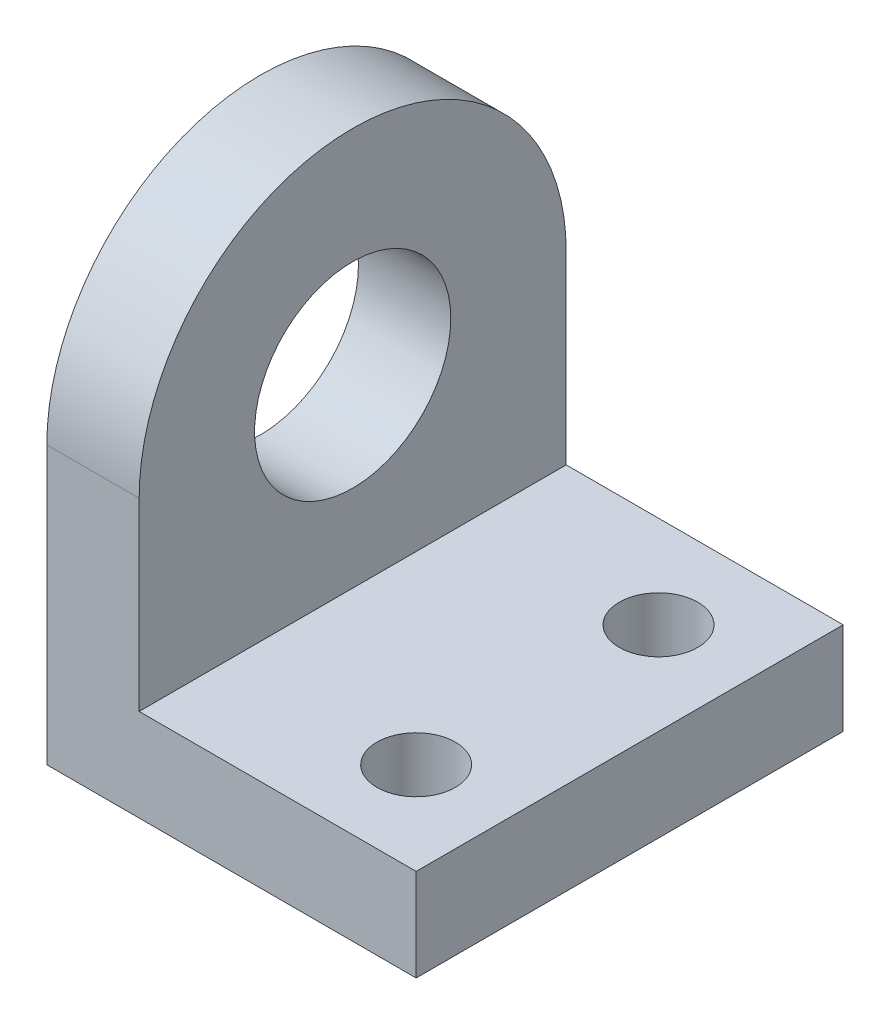
SolidWorks part; units mm, degrees
material "6061 合金"
ref_plane "前视基准面" through (0, 0, 0) normal (0, 0, 1) x (1, 0, 0)
ref_plane "上视基准面" through (0, 0, 0) normal (0, 1, 0) x (1, 0, 0)
ref_plane "右视基准面" through (0, 0, 0) normal (1, 0, 0) x (0, 0, -1)
sketch "草图1" plane through (0, 0, 0) normal (1, 0, 0) x (0, 0, -1)
  line L0 (-9.25, 0) -> (-9.25, -12)
  line L1 (-9.25, 0) -> (9.25, 0) construction
  line L2 (-9.25, -12) -> (9.25, -12)
  line L3 (9.25, 0) -> (9.25, -12)
  line L4 (-9.25, 0) -> (9.25, -12) construction
  line L5 (-9.25, -12) -> (9.25, 0) construction
  circle A0 centre (0, 0) radius 4.25
  arc A1 (-9.25, 0) -> (9.25, 0) centre (0, 0) cw
  point P4 (0, -6)
  dimension "D1" = 8.5
  dimension "D2" = 5
  dimension "D3" = 12
extrude "凸台-拉伸1" add sketch "草图1" along normal blind 4
sketch "草图2" plane through (4, 0, 0) normal (1, 0, 0) x (0, 0, -1)
  line L0 (9.25, -12) -> (9.25, 0) construction
  line L1 (-9.25, -12) -> (9.25, -12)
  line L2 (-9.25, -12) -> (-9.25, -8)
  line L3 (-9.25, -8) -> (9.25, -8)
  line L4 (9.25, -12) -> (9.25, -8)
  dimension "D1" = 4
extrude "凸台-拉伸2" add sketch "草图2" along normal blind 12
hole_wizard "M3 间隙孔1" positions "草图4" profile "草图3" hole size "M3" standard "GB" end condition up to next
sketch "草图4" plane through (0, -8, 0) normal (0, 1, 0) x (1, 0, 0)
  line L0 (0, 0) -> (13.338, 0) construction
  line L2 (16, -9.25) -> (4, -9.25) construction
  line L4 (16, 9.25) -> (16, -9.25) construction
  point P0 (12, 5.25)
  point P2 (12, -5.25)
  dimension "D1" = 4
  dimension "D2" = 4
sketch "草图3" plane through (12, -8, -5.25) normal (1, 0, 0) x (0, 0, 1)
  line L0 (0, 0) -> (0, 4)
  line L1 (0, 4) -> (1.7, 4)
  line L2 (1.7, 4) -> (1.7, 0)
  line L5 (1.7, 0) -> (0, 0)
  line L11 (0, -6.35) -> (0, 107.95) construction
  dimension "通孔孔直径" = 3.4
  dimension "通孔孔深度" = 4
